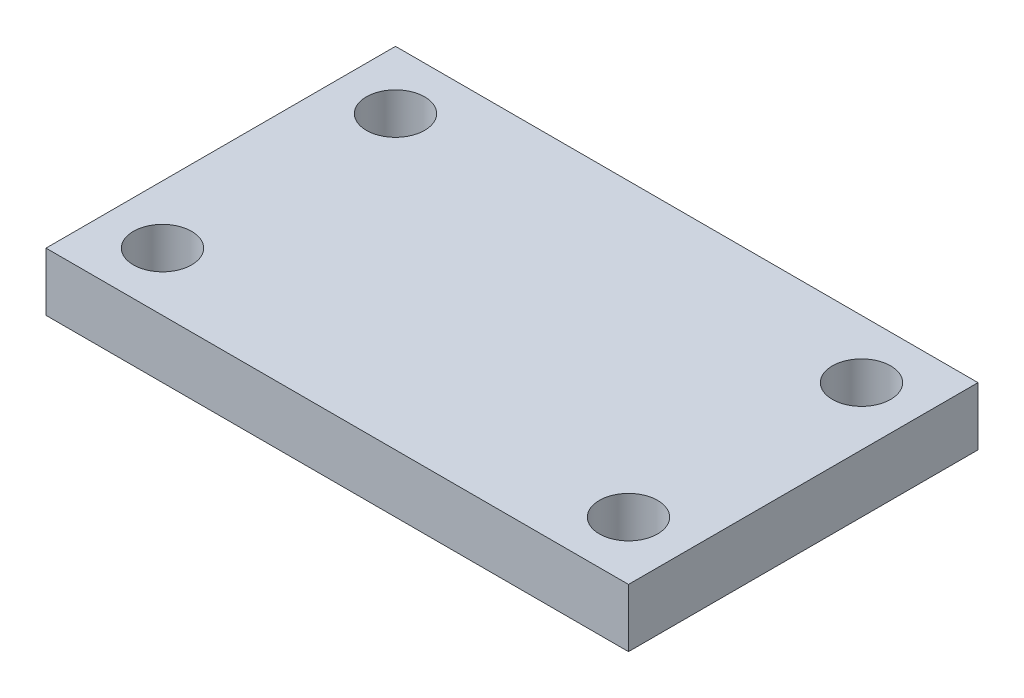
SolidWorks part; units mm, degrees
ref_plane "Front Plane" through (0, 0, 0) normal (0, 0, 1) x (1, 0, 0)
ref_plane "Top Plane" through (0, 0, 0) normal (0, 1, 0) x (1, 0, 0)
ref_plane "Right Plane" through (0, 0, 0) normal (1, 0, 0) x (0, 0, -1)
sketch "Sketch1" plane through (0, 0, 0) normal (0, 1, 0) x (1, 0, 0)
  line L0 (0, 76.2) -> (0, -76.2) construction
  line L1 (-127, 76.2) -> (127, 76.2)
  line L2 (-127, 76.2) -> (-127, -76.2)
  line L3 (-127, -76.2) -> (127, -76.2)
  line L4 (127, 76.2) -> (127, -76.2)
  line L5 (-101.6, 50.8) -> (101.6, 50.8) construction
  line L6 (101.6, 50.8) -> (101.6, -50.8) construction
  line L7 (-101.6, -50.8) -> (101.6, -50.8) construction
  line L8 (-101.6, 50.8) -> (-101.6, -50.8) construction
  circle A0 centre (-101.6, 50.8) radius 12.7
  circle A1 centre (101.6, 50.8) radius 12.7
  circle A2 centre (-101.6, -50.8) radius 12.7
  circle A3 centre (101.6, -50.8) radius 12.7
  dimension "D3" = 25.4
  dimension "D4" = 25.4
  dimension "D1" = 254
  dimension "D2" = 152.4
extrude "Boss-Extrude1" add sketch "Sketch1" along normal blind 25.4
